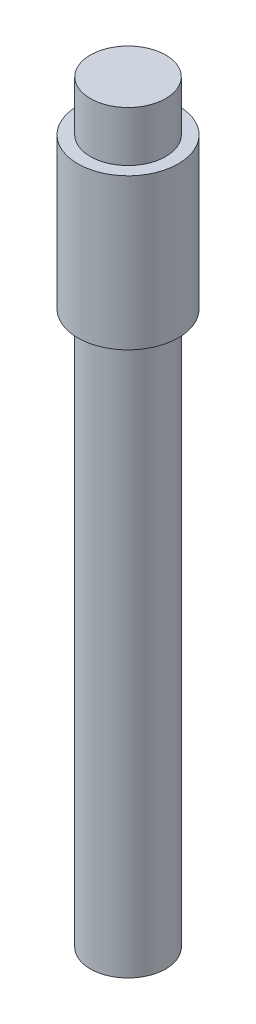
SolidWorks part; units mm, degrees
ref_plane "Front Plane" through (0, 0, 0) normal (0, 0, 1) x (1, 0, 0)
ref_plane "Top Plane" through (0, 0, 0) normal (0, 1, 0) x (1, 0, 0)
ref_plane "Right Plane" through (0, 0, 0) normal (1, 0, 0) x (0, 0, -1)
sketch "Sketch1" plane through (0, 0, 0) normal (0, 0, 1) x (1, 0, 0)
  line L0 (0, -75) -> (0, 75)
  line L1 (0, 75) -> (-7.5, 75)
  line L2 (-7.5, 75) -> (-7.5, 65)
  line L3 (-7.5, 65) -> (-10, 65)
  line L4 (-10, 65) -> (-10, 35)
  line L5 (-10, 35) -> (-7.5, 35)
  line L6 (-7.5, 35) -> (-7.5, -75)
  line L7 (-7.5, -75) -> (0, -75)
  point P4 (0, 0)
  dimension "D1" = 7.5
  dimension "D2" = 10
  dimension "D3" = 10
  dimension "D4" = 30
  dimension "D5" = 150
revolve "Revolve1" add sketch "Sketch1" angle 360 about L0
sketch "Sketch2" plane through (0, -75, 0) normal (0, -1, 0) x (1, 0, 0)
  circle A0 centre (0, 0) radius 4.1
  dimension "D1" = 8.2
extrude "Cut-Extrude1" cut sketch "Sketch2" against normal blind 50
